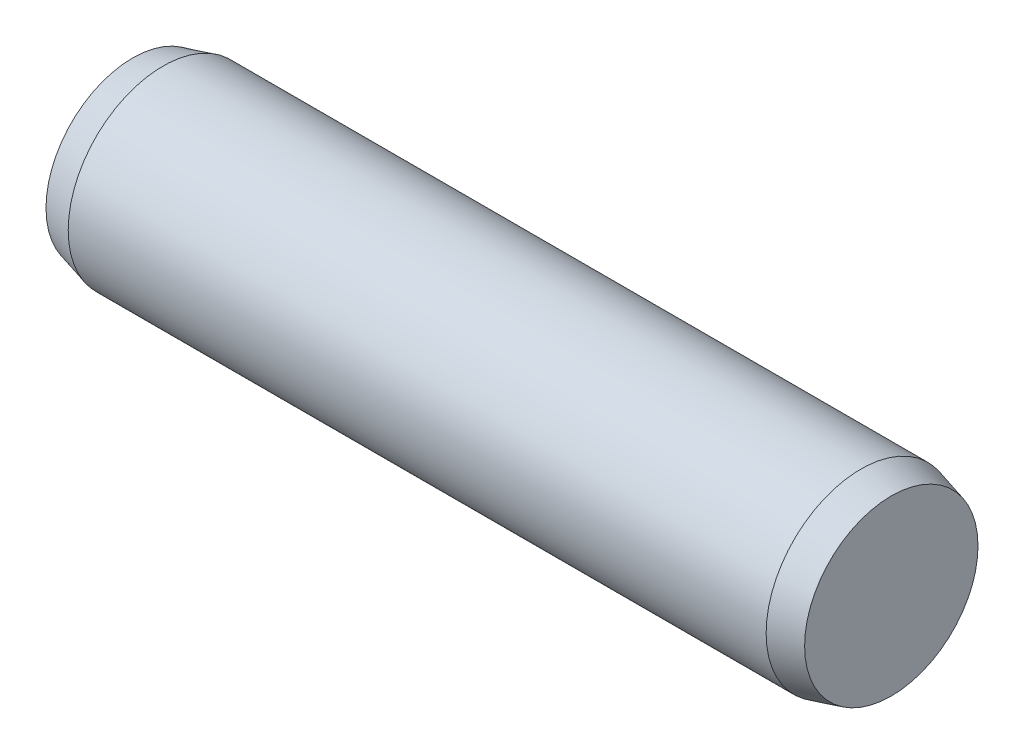
SolidWorks part; units mm, degrees
ref_plane "Plane1" through (0, 0, 0) normal (0, 0, 1) x (1, 0, 0)
ref_plane "Plane2" through (0, 0, 0) normal (0, 1, 0) x (1, 0, 0)
ref_plane "Plane3" through (0, 0, 0) normal (1, 0, 0) x (0, 0, -1)
other "Configuration Table"
sketch "Sketch1" plane through (0, 0, 0) normal (0, 0, 1) x (1, 0, 0)
  line L1 (-6.35, 0) -> (107.95, 0) construction
  line L2 (0, 0) -> (100, 0)
  line L3 (100, 0) -> (100, 11.4282)
  line L4 (100, 11.4282) -> (96, 12.5)
  line L5 (96, 12.5) -> (4, 12.5)
  line L6 (0, 11.4282) -> (0, 0)
  line L7 (0, 11.4282) -> (4, 12.5)
  dimension "D3" = 15
  dimension "D1" = 0.8
  dimension "D2" = 15
revolve "Base-Revolve" add sketch "Sketch1" angle 360 about L1
equation "\"D3@Sketch1\" = 15.0"
equation "\"D1@Sketch1\" = \"Chamfer_len@Sketch1\""
equation "\"D2@Sketch1\" = \"D3@Sketch1\""
